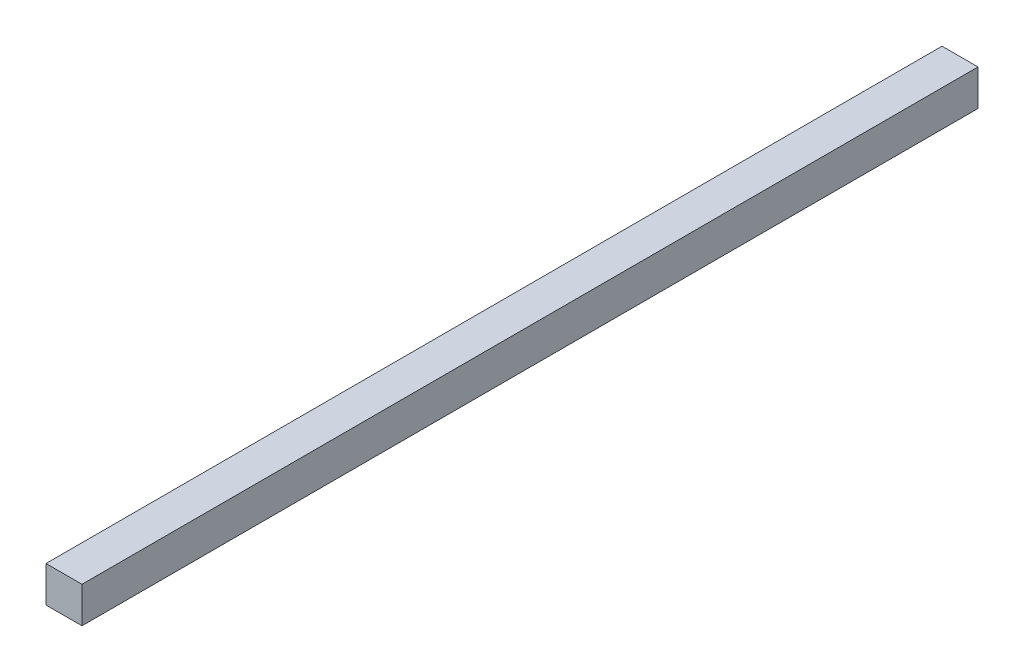
SolidWorks part; units mm, degrees
ref_plane "Front Plane" through (0, 0, 0) normal (0, 0, 1) x (1, 0, 0)
ref_plane "Top Plane" through (0, 0, 0) normal (0, 1, 0) x (1, 0, 0)
ref_plane "Right Plane" through (0, 0, 0) normal (1, 0, 0) x (0, 0, -1)
sketch "Sketch1" plane through (0, 0, 0) normal (0, 0, 1) x (1, 0, 0)
  line L1 (-12.7, 12.7) -> (12.7, 12.7)
  line L2 (-12.7, 12.7) -> (-12.7, -12.7)
  line L3 (-12.7, -12.7) -> (12.7, -12.7)
  line L4 (12.7, 12.7) -> (12.7, -12.7)
  line L5 (-12.7, 12.7) -> (12.7, -12.7) construction
  line L6 (-12.7, -12.7) -> (12.7, 12.7) construction
  point P0 (0, 0)
  dimension "D1" = 25.4
extrude "Boss-Extrude1" add sketch "Sketch1" along normal blind 632.46
